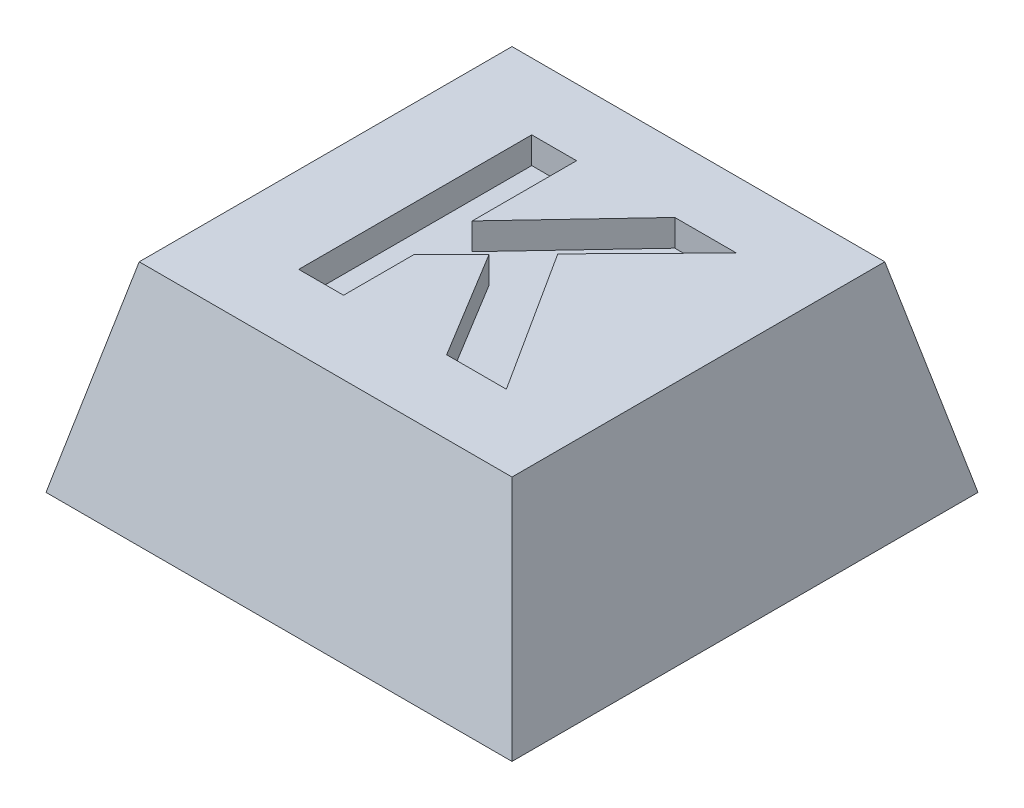
SolidWorks part; units mm, degrees
ref_plane "Front Plane" through (0, 0, 0) normal (0, 0, 1) x (1, 0, 0)
ref_plane "Top Plane" through (0, 0, 0) normal (0, 1, 0) x (1, 0, 0)
ref_plane "Right Plane" through (0, 0, 0) normal (1, 0, 0) x (0, 0, -1)
sketch "Sketch1" plane through (0, 0, 0) normal (0, 1, 0) x (1, 0, 0)
  line L1 (0, 0) -> (7, 0)
  line L2 (0, 0) -> (0, 7)
  line L3 (0, 7) -> (7, 7)
  line L4 (7, 0) -> (7, 7)
  dimension "D1" = 7
  dimension "D2" = 7
extrude "Boss-Extrude1" add sketch "Sketch1" along normal blind 3
sketch "Sketch2" plane through (0, 0, 0) normal (0, 0, 1) x (1, 0, 0)
  line L0 (0, 0) -> (0.7, 3)
  line L1 (0, 3) -> (7, 3) construction
  line L2 (0.7, 3) -> (0, 3)
  line L3 (0, 3) -> (0, 0)
  line L4 (7, 0) -> (6.3, 3)
  line L5 (6.3, 3) -> (7, 3)
  line L6 (7, 3) -> (7, 0)
  dimension "D1" = 0.7
  dimension "D2" = 0.7
extrude "Cut-Extrude1" cut sketch "Sketch2" against normal blind 7
sketch "Sketch3" plane through (0, 0, 0) normal (1, 0, 0) x (0, 0, -1)
  line L0 (0, 0) -> (0.7, 3)
  line L1 (7, 3) -> (0, 3) construction
  line L2 (0.7, 3) -> (0, 3)
  line L3 (0, 3) -> (0, 0)
  line L4 (7, 3) -> (6.3, 3)
  line L5 (6.3, 3) -> (7, 0)
  line L6 (7, 3) -> (7, 0)
  dimension "D1" = 0.7
  dimension "D2" = 0.7
extrude "Cut-Extrude2" cut sketch "Sketch3" along normal blind 11
sketch "Sketch4" plane through (0, 0, 0) normal (0, -1, 0) x (1, 0, 0)
  line L0 (3.5, 0) -> (3.5, -7) construction
  line L1 (0, 0) -> (7, 0) construction
  line L2 (7, -7) -> (0, -7) construction
  line L3 (0, -3.5) -> (7, -3.5) construction
  line L4 (0, -7) -> (0, 0) construction
  line L5 (7, 0) -> (7, -7) construction
  circle A0 centre (3.5, -3.5) radius 1.8
  dimension "D1" = 3.6
extrude "Cut-Extrude3" cut sketch "Sketch4" against normal blind 0.8
sketch "Sketch5" plane through (0, 3, 0) normal (0, 1, 0) x (1, 0, 0)
  text T0 "K" font "Arial" height 3.5
extrude "Cut-Extrude4" cut sketch "Sketch5" against normal blind 0.4
